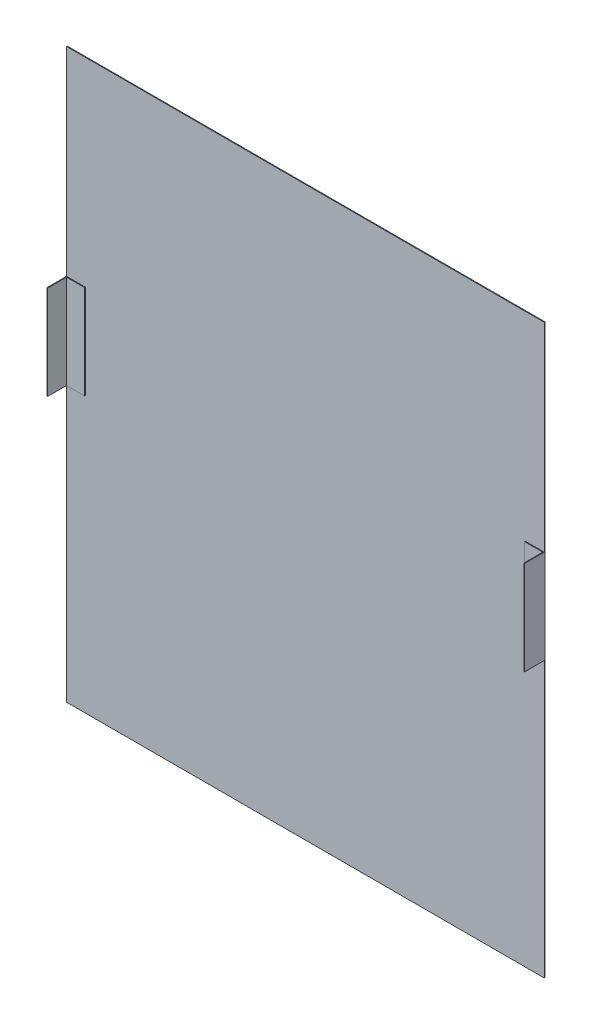
SolidWorks part; units mm, degrees
ref_plane "Front Plane" through (0, 0, 0) normal (0, 0, 1) x (1, 0, 0)
ref_plane "Top Plane" through (0, 0, 0) normal (0, 1, 0) x (1, 0, 0)
ref_plane "Right Plane" through (0, 0, 0) normal (1, 0, 0) x (0, 0, -1)
sketch "Sketch1" plane through (0, 0, 0) normal (0, 0, 1) x (1, 0, 0)
  line L1 (0, 0) -> (509, 0)
  line L2 (0, 0) -> (0, 605)
  line L3 (0, 605) -> (509, 605)
  line L4 (509, 0) -> (509, 605)
extrude "Boss-Extrude1" add sketch "Sketch1" along normal blind 0.8
sketch "Sketch2" plane through (0, 0, 0.8) normal (0, 0, 1) x (1, 0, 0)
  line L0 (0, 605) -> (0, 0) construction
  line L1 (0, 392.9188) -> (20, 392.9188)
  line L2 (0, 392.9188) -> (0, 292.9188)
  line L3 (0, 292.9188) -> (20, 292.9188)
  line L4 (20, 392.9188) -> (20, 292.9188)
  line L5 (489, 392.9188) -> (509, 392.9188)
  line L6 (509, 0) -> (509, 605) construction
  line L8 (509, 392.9188) -> (489, 392.9188)
  line L9 (509, 392.9188) -> (509, 292.9188)
  line L10 (509, 292.9188) -> (489, 292.9188)
  line L11 (489, 392.9188) -> (489, 292.9188)
  line M5 (0, 605) -> (0, 0)
  line M7 (509, 0) -> (509, 605)
extrude "Boss-Extrude2" add sketch "Sketch2" along normal blind 0.8 contours L4 L1 L3 M5 | L5 L11 L10 M7
ref_plane "Plane1" through (0, 0, 0) normal (-1, 0, 0) x (0, 0, 1)
sketch "Sketch4" plane through (0, 0, 0) normal (-1, 0, 0) x (0, 0, 1)
  line L1 (1.6, 392.9188) -> (21.6, 392.9188)
  line L2 (1.6, 392.9188) -> (1.6, 292.9188)
  line L3 (1.6, 292.9188) -> (21.6, 292.9188)
  line L4 (21.6, 392.9188) -> (21.6, 292.9188)
extrude "Boss-Extrude3" add sketch "Sketch4" against normal blind 0.8
ref_plane "Plane2" through (509, 0, 0) normal (1, 0, 0) x (0, 0, -1)
sketch "Sketch5" plane through (509, 0, 0) normal (1, 0, 0) x (0, 0, -1)
  line L1 (-1.6, 392.9188) -> (-21.6, 392.9188)
  line L2 (-1.6, 392.9188) -> (-1.6, 292.9188)
  line L3 (-1.6, 292.9188) -> (-21.6, 292.9188)
  line L4 (-21.6, 392.9188) -> (-21.6, 292.9188)
extrude "Boss-Extrude4" add sketch "Sketch5" against normal blind 0.8
